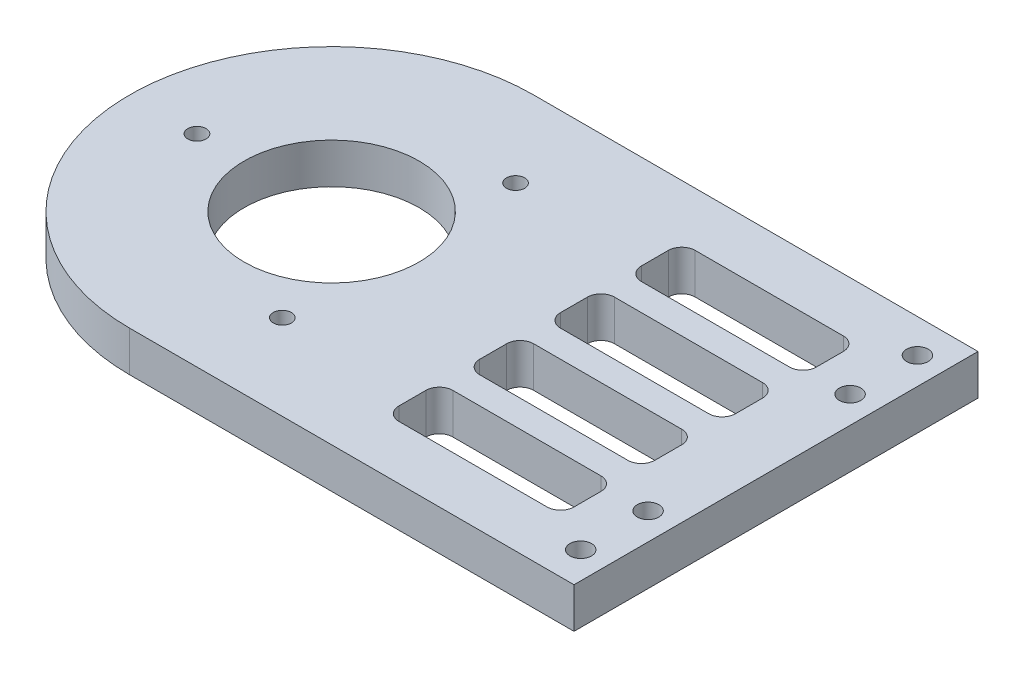
SolidWorks part; units mm, degrees
material "Thornel Mat VMA"
ref_plane "前视基准面" through (0, 0, 0) normal (0, 0, 1) x (1, 0, 0)
ref_plane "上视基准面" through (0, 0, 0) normal (0, 1, 0) x (1, 0, 0)
ref_plane "右视基准面" through (0, 0, 0) normal (1, 0, 0) x (0, 0, -1)
other "Configuration Table"
sketch "草图1" plane through (0, 0, 0) normal (0, 1, 0) x (1, 0, 0)
  line L1 (-33, -30) -> (33, -30)
  line L3 (-33, 30) -> (33, 30)
  line L4 (33, -30) -> (33, 30)
  line L5 (-33, -30) -> (33, 30) construction
  line L6 (-33, 30) -> (33, -30) construction
  arc A0 (-33, 30) -> (-33, -30) centre (-33, 0) ccw
  point P0 (0, 0)
  dimension "D2" = 30
  dimension "D1" = 66
extrude "凸台-拉伸1" add sketch "草图1" along normal blind 6
sketch "草图2" plane through (0, 6, 0) normal (0, 1, 0) x (1, 0, 0)
  line L3 (33, -30) -> (33, 30)
  line L4 (33, 30) -> (-33, 30)
  line L5 (-33, -30) -> (33, -30)
  line L6 (33, -30) -> (33, 30) construction
  line L7 (33, 30) -> (-33, 30) construction
  line L8 (-33, -30) -> (33, -30) construction
  circle A0 centre (-33, 0) radius 13
  arc A1 (-33, 30) -> (-33, -30) centre (-33, 0) ccw
  arc A2 (-33, 30) -> (-33, -30) centre (-33, 0) ccw construction
  circle A3 centre (-53, 0) radius 1.35
  circle A4 centre (-23, 17.3205) radius 1.35
  circle A5 centre (-23, -17.3205) radius 1.35
  point P15 (-33, 0)
  dimension "D2" = 26
  dimension "D4" = 2.7
  dimension "D3" = 20
  dimension "D1" = 0
  dimension "D5" = 3
extrude "切除-拉伸1" cut sketch "草图2" against normal up to surface (6 mm away) up to face at (-7.5, 0, 0)
sketch "草图3" plane through (0, 6, 0) normal (0, 1, 0) x (1, 0, 0)
  line L0 (-3, 30) -> (-3, -30.9307) construction
  line L2 (21, 14) -> (-1, 14)
  line L3 (33, -30) -> (33, 30)
  line L4 (33, 30) -> (-33, 30)
  line L5 (-33, -30) -> (33, -30)
  line L6 (33, -30) -> (33, 30) construction
  line L7 (33, 30) -> (-33, 30) construction
  line L8 (-33, -30) -> (33, -30) construction
  line L9 (23, 16) -> (23, 20)
  line L10 (21, 22) -> (-1, 22)
  line L11 (-3, 16) -> (-3, 20)
  line L12 (23, 14) -> (-3, 22) construction
  line L13 (23, 22) -> (-3, 14) construction
  line L29 (23, 4) -> (23, 8)
  line L30 (21, 2) -> (-1, 2)
  line L31 (-3, 4) -> (-3, 8)
  line L32 (21, 10) -> (-1, 10)
  line L33 (23, -8) -> (23, -4)
  line L34 (21, -10) -> (-1, -10)
  line L35 (-3, -8) -> (-3, -4)
  line L36 (21, -2) -> (-1, -2)
  line L37 (23, -20) -> (23, -16)
  line L38 (21, -22) -> (-1, -22)
  line L39 (-3, -20) -> (-3, -16)
  line L40 (21, -14) -> (-1, -14)
  circle A0 centre (-33, 0) radius 30 construction
  arc A1 (-33, 30) -> (-33, -30) centre (-33, 0) ccw
  arc A2 (-33, 30) -> (-33, -30) centre (-33, 0) ccw construction
  arc A3 (-3, -16) -> (-1, -14) centre (-1, -16) cw
  arc A4 (-1, -22) -> (-3, -20) centre (-1, -20) cw
  arc A5 (23, -20) -> (21, -22) centre (21, -20) cw
  arc A6 (23, -16) -> (21, -14) centre (21, -16) ccw
  arc A7 (23, -4) -> (21, -2) centre (21, -4) ccw
  arc A8 (23, -8) -> (21, -10) centre (21, -8) cw
  arc A9 (-1, -10) -> (-3, -8) centre (-1, -8) cw
  arc A10 (-3, -4) -> (-1, -2) centre (-1, -4) cw
  arc A11 (23, 8) -> (21, 10) centre (21, 8) ccw
  arc A12 (23, 4) -> (21, 2) centre (21, 4) cw
  arc A13 (-1, 2) -> (-3, 4) centre (-1, 4) cw
  arc A14 (-3, 8) -> (-1, 10) centre (-1, 8) cw
  arc A15 (23, 20) -> (21, 22) centre (21, 20) ccw
  arc A16 (21, 14) -> (23, 16) centre (21, 16) ccw
  arc A17 (-1, 14) -> (-3, 16) centre (-1, 16) cw
  arc A18 (-1, 22) -> (-3, 20) centre (-1, 20) ccw
  point P9 (10, 18)
  dimension "D7" = 2
  dimension "D2" = 10
  dimension "D3" = 8
  dimension "D4" = 8
  dimension "D6" = 8
  dimension "D1" = 0
  dimension "D5" = 4
extrude "切除-拉伸2" cut sketch "草图3" against normal up to surface (6 mm away) up to face at (-23, 0, 18.6705)
sketch "草图4" plane through (0, 6, 0) normal (0, 1, 0) x (1, 0, 0)
  line L0 (-77.9698, 0) -> (38.6165, 0) construction
  line L3 (33, -30) -> (33, 30)
  line L4 (33, 30) -> (-33, 30)
  line L5 (-33, -30) -> (33, -30)
  line L6 (33, -30) -> (33, 30) construction
  line L7 (33, 30) -> (-33, 30) construction
  line L8 (-33, -30) -> (33, -30) construction
  circle A0 centre (29, 25) radius 1.6
  arc A1 (-33, 30) -> (-33, -30) centre (-33, 0) ccw
  arc A2 (-33, 30) -> (-33, -30) centre (-33, 0) ccw construction
  circle A3 centre (29, 15) radius 1.6
  circle A4 centre (29, -25) radius 1.6
  circle A5 centre (29, -15) radius 1.6
  dimension "D2" = 3.2
  dimension "D3" = 3.2
  dimension "D4" = 5
  dimension "D5" = 10
  dimension "D6" = 4
  dimension "D1" = 0
extrude "切除-拉伸3" cut sketch "草图4" against normal up to surface (6 mm away) up to face at (10, 0, 18)
